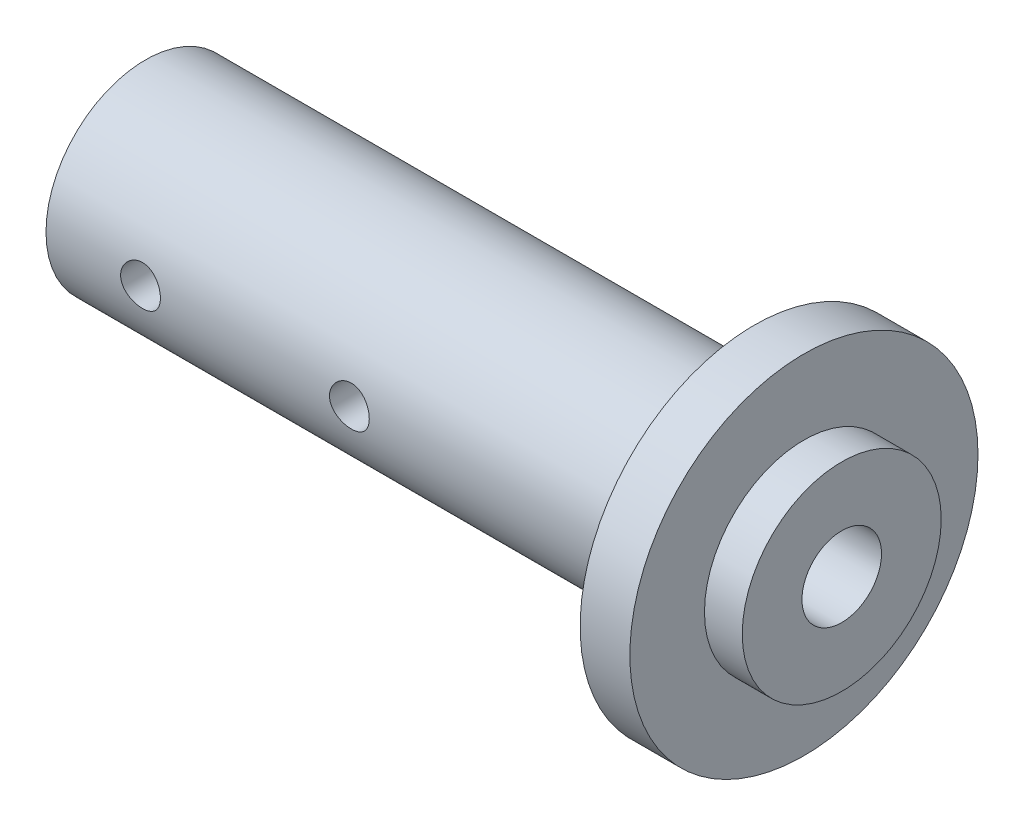
SolidWorks part; units mm, degrees
ref_plane "Front Plane" through (0, 0, 0) normal (0, 0, 1) x (1, 0, 0)
ref_plane "Top Plane" through (0, 0, 0) normal (0, 1, 0) x (1, 0, 0)
ref_plane "Right Plane" through (0, 0, 0) normal (1, 0, 0) x (0, 0, -1)
sketch "Sketch1" plane through (0, 0, 0) normal (0, 1, 0) x (1, 0, 0)
  line L1 (-3.8, 17.5) -> (-8.8, 17.5)
  line L2 (-8.8, 17.5) -> (-8.8, 10)
  line L3 (-8.8, 10) -> (-70, 10)
  line L4 (-70, 10) -> (-70, 0)
  line L5 (-70, 0) -> (0, 0) construction
  line L6 (0, 0) -> (-70, 0)
  line L7 (-3.8, 17.5) -> (-3.8, 10)
  line L8 (-3.8, 10) -> (0, 10)
  line L9 (0, 10) -> (0, 4)
  line L10 (0, 4) -> (-19, 4)
  line L11 (-19, 4) -> (-19, 0)
  dimension "D1" = 5
  dimension "D2" = 17.5
  dimension "D3" = 10
  dimension "D4" = 70
  dimension "D5" = 3.8
  dimension "D6" = 4
  dimension "D7" = 19
revolve "Revolve2" add sketch "Sketch1" angle 360 about L6
ref_plane "Plane2" [suppressed] through (0, 7.0711, 7.0711) normal (0, 0.7071, 0.7071) x (1, 0, 0)
hole_wizard "M4 Tapped Hole1" [suppressed] positions "Sketch3" profile "Sketch4" tap size "M4" standard "ISO"
sketch "Sketch3" [suppressed] plane through (0, 7.0711, 7.0711) normal (0, 0.7071, 0.7071) x (1, 0, 0)
  line L0 (-8.8, 17.5) -> (-8.8, -17.5) construction
  point P0 (-14.8, 0)
  dimension "D1" = 6
sketch "Sketch4" plane through (-14.8, 7.0711, 7.0711) normal (1, 0, 0) x (0, -0.7071, 0.7071)
  line L0 (0, 0) -> (0, 206242.2201)
  line L1 (0, 206242.2201) -> (1.65, 206241.2287)
  line L2 (1.65, 206241.2287) -> (1.65, 0)
  line L5 (1.65, 0) -> (0, 0)
  line L10 (0, 206242.2201) -> (-1.65, 206241.2287) construction
  line L11 (0, -6.35) -> (0, 107.95) construction
  dimension "Tap Drill Dia." = 3.3
  dimension "Tap Drill Depth" = 206241.2287
  dimension "Drill Angle" = 118
cosmetic thread "Hole Thread1" [suppressed] parameters "D1"=8, "D2"=4
sketch "Sketch5" plane through (0, 0, 0) normal (0, 0, 1) x (1, 0, 0)
  circle A0 centre (-39.5, 0) radius 2
  circle A1 centre (-60.5, 0) radius 2
  circle A2 centre (-39.5, 0) radius 2 construction
  circle A3 centre (-60.5, 0) radius 2 construction
extrude "Cut-Extrude2" cut sketch "Sketch5" against normal through all both and the other way through all
